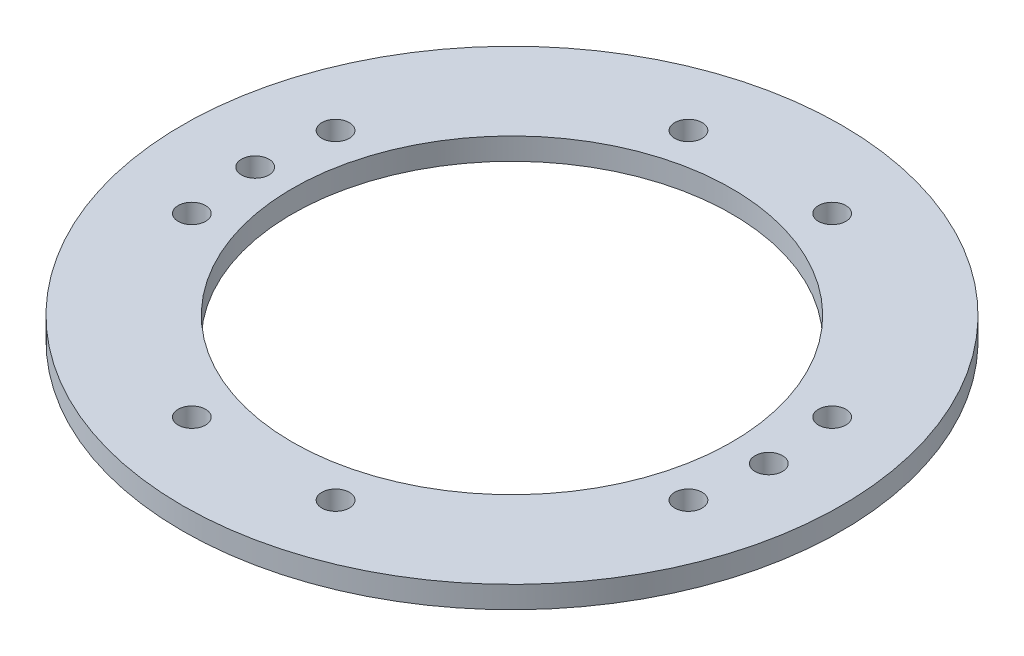
SolidWorks part; units mm, degrees
ref_plane "Front Plane" through (0, 0, 0) normal (0, 0, 1) x (1, 0, 0)
ref_plane "Top Plane" through (0, 0, 0) normal (0, 1, 0) x (1, 0, 0)
ref_plane "Right Plane" through (0, 0, 0) normal (1, 0, 0) x (0, 0, -1)
sketch "Sketch1" plane through (0, 0, 0) normal (0, 1, 0) x (1, 0, 0)
  line L0 (0, 0) -> (0, 76.2) construction
  line L1 (-16.6168, 57.412) -> (0, 57.412) construction
  line L2 (0, 0) -> (-76.2, 0) construction
  line L3 (0, 57.412) -> (16.6168, 57.412) construction
  circle A0 centre (0, 0) radius 76.2
  circle A1 centre (0, 0) radius 50.8
  circle A2 centre (-16.6168, 57.412) radius 3.175
  circle A3 centre (16.6168, 57.412) radius 3.175
  circle A4 centre (57.412, 16.6168) radius 3.175
  circle A5 centre (16.6168, -57.412) radius 3.175
  circle A6 centre (-57.412, -16.6168) radius 3.175
  circle A7 centre (57.412, -16.6168) radius 3.175
  circle A8 centre (-16.6168, -57.412) radius 3.175
  circle A9 centre (-57.412, 16.6168) radius 3.175
  circle A10 centre (-59.3724, 0) radius 3.175
  circle A11 centre (59.3724, 0) radius 3.175
  point P20 (0, 0)
  point P27 (0, 0)
  point P32 (0, 0)
  dimension "D1" = 152.4
  dimension "D2" = 4
  dimension "D4" = 2
  dimension "D5" = 6.35
  dimension "D3" = 4
extrude "Boss-Extrude1" add sketch "Sketch1" along normal blind 5.08
